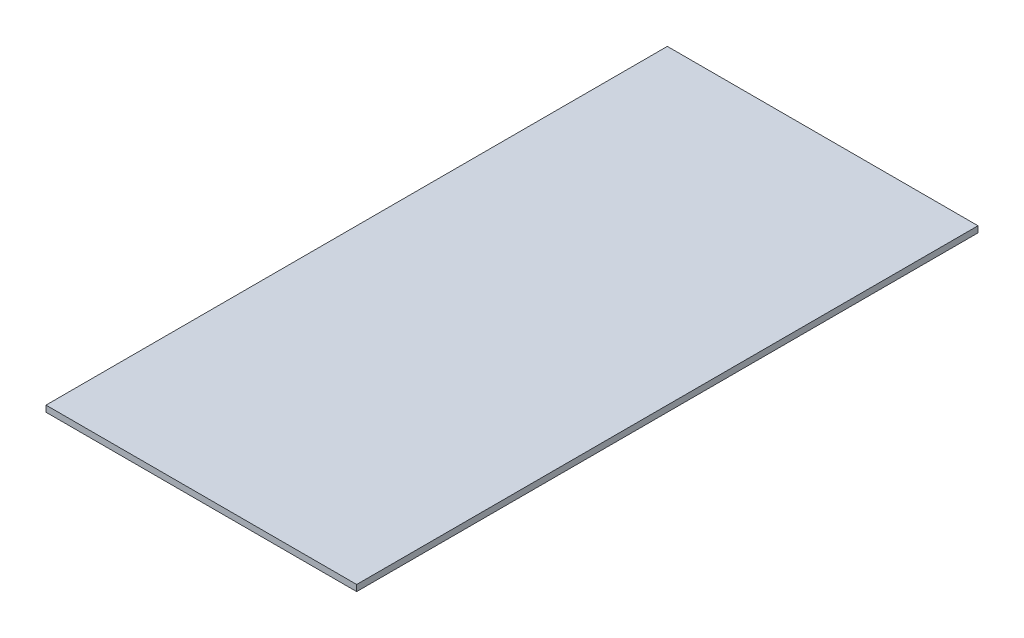
SolidWorks part; units mm, degrees
ref_plane "Front Plane" through (0, 0, 0) normal (0, 0, 1) x (1, 0, 0)
ref_plane "Top Plane" through (0, 0, 0) normal (0, 1, 0) x (1, 0, 0)
ref_plane "Right Plane" through (0, 0, 0) normal (1, 0, 0) x (0, 0, -1)
sketch "Sketch1" plane through (0, 0, 0) normal (0, 1, 0) x (1, 0, 0)
  line L0 (130.175, 0) -> (158.75, 0)
  line L1 (0, 0) -> (28.575, 0)
  line L2 (0, 0) -> (0, 317.5)
  line L3 (0, 317.5) -> (158.75, 317.5)
  line L4 (158.75, 0) -> (158.75, 317.5)
  line L6 (28.575, 0) -> (28.575, -3.175) construction
  line L7 (28.575, -3.175) -> (130.175, -3.175) construction
  line L8 (130.175, 0) -> (130.175, -3.175) construction
  line L9 (28.575, 0) -> (130.175, 0)
  point P9 (79.375, -3.175)
  point P10 (79.375, 317.5)
  dimension "D1" = 158.75
  dimension "D2" = 317.5
  dimension "D3" = 3.175
  dimension "D4" = 101.6
extrude "Boss-Extrude1" add sketch "Sketch1" along normal blind 3.175
